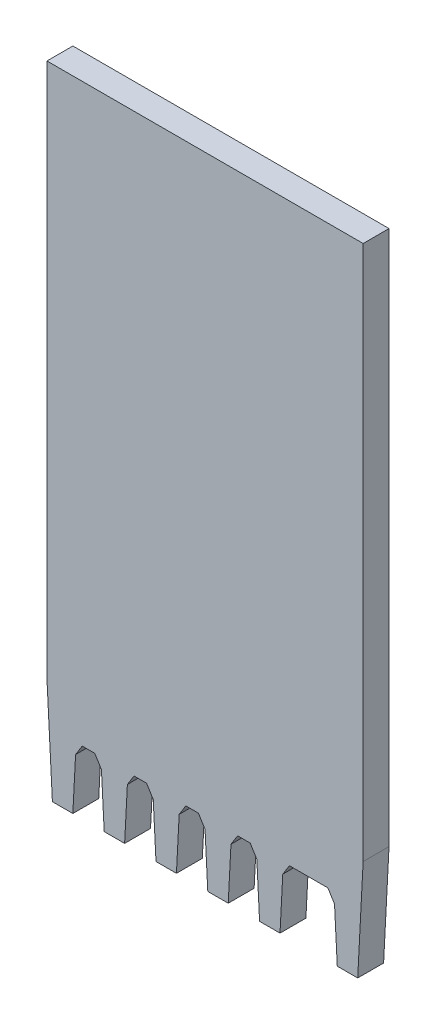
SolidWorks part; units mm, degrees
ref_plane "Front Plane" through (0, 0, 0) normal (0, 0, 1) x (1, 0, 0)
ref_plane "Top Plane" through (0, 0, 0) normal (0, 1, 0) x (1, 0, 0)
ref_plane "Right Plane" through (0, 0, 0) normal (1, 0, 0) x (0, 0, -1)
sketch "Sketch1" plane through (0, 0, 0) normal (0, 0, 1) x (1, 0, 0)
  line L0 (0, 0) -> (0, 37) construction
  line L1 (0, 37) -> (18.3124, 37) construction
  line L2 (18.3124, 37) -> (18.3124, 0) construction
  line L3 (18.3124, 0) -> (0, 0) construction
  line L4 (0, 3) -> (18.3124, 3) construction
  line L5 (0, 6) -> (18.3124, 6) construction
  line L6 (0.9062, 6) -> (0.9062, 0) construction
  line L7 (3.9062, 6) -> (3.9062, 0) construction
  line L8 (6.9062, 6) -> (6.9062, 0) construction
  line L9 (9.9062, 6) -> (9.9062, 0) construction
  line L10 (12.9062, 6) -> (12.9062, 0) construction
  line L11 (17.4062, 6) -> (17.4062, 0) construction
  line L12 (0.9062, 3) -> (3.9062, 3) construction
  line L13 (3.9062, 3) -> (6.9062, 3) construction
  line L14 (6.9062, 3) -> (9.9062, 3) construction
  line L15 (9.9062, 3) -> (12.9062, 3) construction
  line L16 (12.9062, 3) -> (17.4062, 3) construction
  line L17 (0.9062, 3) -> (0, 3) construction
  line L18 (17.4062, 3) -> (18.3124, 3) construction
  line L19 (2.4062, 3) -> (2.4062, 0) construction
  line L20 (5.4062, 3) -> (5.4062, 0) construction
  line L21 (8.4062, 3) -> (8.4062, 0) construction
  line L22 (11.4062, 3) -> (11.4062, 0) construction
  line L23 (15.1562, 3) -> (15.1562, 0) construction
  line L24 (14.4062, 3.75) -> (15.9062, 3.75) construction
  line L25 (0, 6) -> (0.3144, 0)
  line L26 (0.3144, 0) -> (1.4979, 0)
  line L27 (1.4979, 0) -> (1.6572, 3.0393)
  line L28 (3.1552, 3.0393) -> (3.3144, 0)
  line L29 (3.3144, 0) -> (4.4979, 0)
  line L30 (4.4979, 0) -> (4.6572, 3.0393)
  line L31 (6.1552, 3.0393) -> (6.3144, 0)
  line L32 (6.3144, 0) -> (7.4979, 0)
  line L33 (7.4979, 0) -> (7.6572, 3.0393)
  line L34 (9.1552, 3.0393) -> (9.3144, 0)
  line L35 (9.3144, 0) -> (10.4979, 0)
  line L36 (10.4979, 0) -> (10.6572, 3.0393)
  line L37 (12.1552, 3.0393) -> (12.3144, 0)
  line L38 (12.3144, 0) -> (13.4979, 0)
  line L39 (13.4979, 0) -> (13.6572, 3.0393)
  line L40 (16.6552, 3.0393) -> (16.8144, 0)
  line L41 (16.8144, 0) -> (17.9979, 0)
  line L42 (17.9979, 0) -> (18.3124, 6)
  line L44 (1.6572, 3.0393) -> (2.0426, 3.656)
  line L45 (0, 6) -> (0, 37)
  line L46 (0, 37) -> (18.3124, 37)
  line L47 (18.3124, 37) -> (18.3124, 6)
  line L48 (9.1562, 37) -> (9.1562, 6) construction
  line L49 (2.0426, 3.656) -> (2.7698, 3.656)
  line L50 (2.7698, 3.656) -> (3.1552, 3.0393)
  line L51 (4.6572, 3.0393) -> (5.0426, 3.656)
  line L52 (5.0426, 3.656) -> (5.7698, 3.656)
  line L53 (5.7698, 3.656) -> (6.1552, 3.0393)
  line L54 (7.6572, 3.0393) -> (8.0426, 3.656)
  line L55 (8.0426, 3.656) -> (8.7698, 3.656)
  line L56 (8.7698, 3.656) -> (9.1552, 3.0393)
  line L57 (10.6572, 3.0393) -> (11.0426, 3.656)
  line L58 (11.0426, 3.656) -> (11.7698, 3.656)
  line L59 (11.7698, 3.656) -> (12.1552, 3.0393)
  line L60 (13.6572, 3.0393) -> (14.0426, 3.656)
  line L61 (14.0426, 3.656) -> (16.2698, 3.656)
  line L62 (16.2698, 3.656) -> (16.6552, 3.0393)
  arc A0 (3.1552, 3.0393) -> (1.6572, 3.0393) centre (2.4062, 3) ccw construction
  arc A1 (6.1552, 3.0393) -> (4.6572, 3.0393) centre (5.4062, 3) ccw construction
  arc A2 (9.1552, 3.0393) -> (7.6572, 3.0393) centre (8.4062, 3) ccw construction
  arc A3 (12.1552, 3.0393) -> (10.6572, 3.0393) centre (11.4062, 3) ccw construction
  arc A4 (13.6572, 3.0393) -> (14.4062, 3.75) centre (14.4062, 3) cw construction
  arc A5 (16.6552, 3.0393) -> (15.9062, 3.75) centre (15.9062, 3) ccw construction
  dimension "D7" = 0.75
  dimension "D1" = 3
  dimension "D2" = 6
  dimension "D3" = 31
  dimension "D4" = 3
  dimension "D6" = 4.5
  dimension "D8" = 3
  dimension "D9" = 18.3124
  dimension "D10" = 37
extrude "Boss-Extrude1" add sketch "Sketch1" along normal blind 1.5
sketch "Sketch3" plane through (0, 0, 0) normal (0, 0, 1) x (1, 0, 0)
  line L0 (-0.4005, 6) -> (18.7129, 6)
  line L1 (18.7129, 3) -> (-0.4005, 3) construction
  line L2 (-0.4005, 0) -> (18.7129, 0) construction
  line L3 (-0.4005, -0.5) -> (18.7129, -0.5) construction
  line L4 (18.7129, -0.5) -> (18.7129, 6) construction
  line L5 (-0.4005, 6) -> (-0.4005, -0.5) construction
  line L6 (18.3124, 0) -> (0, 0) construction
  line L7 (0, 3) -> (18.3124, 3) construction
  line L8 (0, 6) -> (18.3124, 6) construction
  line L9 (0.3407, -0.5) -> (0, 6) construction
  line L10 (18.3124, 6) -> (17.9717, -0.5) construction
  line L11 (17.9979, 0) -> (18.3124, 6) construction
  line L12 (0, 6) -> (0.3144, 0) construction
  line L13 (5.4062, 6) -> (5.4062, -0.5) construction
  line L14 (3.9062, 6) -> (3.9062, -0.5) construction
  line L15 (5.4062, 3) -> (5.4062, 0) construction
  line L16 (3.1572, 3) -> (3.3407, -0.5) construction
  line L17 (2.7567, 3) -> (2.9401, -0.5)
  line L18 (3.1552, 3.0393) -> (3.3144, 0) construction
  line L19 (2.9401, -0.5) -> (4.8723, -0.5)
  line L20 (4.8723, -0.5) -> (5.0557, 3)
  line L21 (2.8484, 1.25) -> (3.2478, 1.2709) construction
  line L22 (5.9401, -0.5) -> (5.7567, 3)
  line L26 (7.8723, -0.5) -> (5.9401, -0.5)
  line L27 (8.0557, 3) -> (7.8723, -0.5)
  line L30 (2.4062, -0.5) -> (2.4062, 6) construction
  line L31 (2.4062, 3) -> (2.4062, 0) construction
  line L32 (8.4062, 6) -> (8.4062, -0.5) construction
  line L34 (11.4062, -0.5) -> (11.4062, 6) construction
  line L35 (15.1562, -0.5) -> (15.1562, 6) construction
  line L36 (8.4062, 3) -> (8.4062, 0) construction
  line L37 (11.4062, 3) -> (11.4062, 0) construction
  line L38 (15.1562, 3) -> (15.1562, 0) construction
  line L39 (10.8723, -0.5) -> (11.0557, 3)
  line L40 (8.9401, -0.5) -> (10.8723, -0.5)
  line L41 (8.7567, 3) -> (8.9401, -0.5)
  line L42 (11.9401, -0.5) -> (11.7567, 3)
  line L43 (13.8723, -0.5) -> (11.9401, -0.5)
  line L44 (14.0557, 3) -> (13.8723, -0.5)
  line L45 (16.4401, -0.5) -> (18.3723, -0.5)
  line L46 (16.2567, 3) -> (16.4401, -0.5)
  line L47 (18.3723, -0.5) -> (18.7129, 6)
  line L48 (1.8723, -0.5) -> (-0.0599, -0.5)
  line L49 (2.0557, 3) -> (1.8723, -0.5)
  line L50 (-0.0599, -0.5) -> (-0.4005, 6)
  line L51 (16.2567, 3) -> (14.0557, 3)
  line L52 (11.7567, 3) -> (11.0557, 3)
  line L53 (8.7567, 3) -> (8.0557, 3)
  line L54 (5.7567, 3) -> (5.0557, 3)
  line L55 (2.7567, 3) -> (2.0557, 3)
  dimension "D1" = 0.5
  dimension "D2" = 0.4
ref_plane "Plane1" through (3.9062, 0, 0) normal (1, 0, 0) x (0, 0, -1)
sketch "Sketch4" plane through (3.9062, 0, 0) normal (1, 0, 0) x (0, 0, -1)
  line L0 (0, 6) -> (0, -0.5) construction
  line L1 (0.6, 6) -> (-2.1, 6) construction
  line L2 (0.6, 6) -> (0.6, -0.5) construction
  line L3 (0.6, -0.5) -> (-2.1, -0.5) construction
  line L4 (-2.1, 6) -> (-2.1, -0.5) construction
  line L5 (-0.75, -0.5) -> (-0.75, 6) construction
  line L6 (-1.5, 6) -> (-1.5, -0.5) construction
  line L7 (0.6, 2.4005) -> (-2.1, 2.4005) construction
  line L8 (0.3, 6) -> (0.3, -0.5) construction
  line L9 (0.6, 2.4005) -> (3.846, 6) construction
  line L10 (2.2302, 6) -> (0.6, 4.1923) construction
  line L11 (0.6, 4.1923) -> (1.7139, 3.1878) construction
  line L12 (1.7139, 3.1878) -> (4.25, 6)
  line L13 (4.25, 6) -> (0.6, 6) construction
  line L14 (0.3, 1) -> (-1.8, 1) construction
  line L15 (-2.1, 0) -> (0.6, 0) construction
  line L16 (1.7139, 3.1878) -> (1.4912, 3.3887)
  line L17 (1.4912, 3.3887) -> (0.6, 2.4005)
  line L18 (-3.2139, 3.1878) -> (-5.75, 6)
  line L19 (-3.2139, 3.1878) -> (-2.9912, 3.3887)
  line L20 (-2.9912, 3.3887) -> (-2.1, 2.4005)
  line L21 (-2.1, 6) -> (-5.75, 6) construction
  line L22 (0.6, 3.0724) -> (3.2401, 6) construction
  arc A0 (0.4965, 2.2224) -> (0.6, -0.5) centre (4.2, 1) ccw
  arc A1 (0.6, 2.4005) -> (0.4965, 2.2224) centre (0.9713, 2.0656) ccw
  arc A2 (-2.1, 2.4005) -> (-1.9965, 2.2224) centre (-2.4713, 2.0656) cw
  arc A3 (-1.9965, 2.2224) -> (-2.1, -0.5) centre (-5.7, 1) cw
  dimension "D6" = 0.5
  dimension "D1" = 0.6
  dimension "D2" = 0.3
  dimension "D3" = 1.5
  dimension "D4" = 1
  dimension "D5" = 0.3
  dimension "D7" = 10
sketch "Sketch5" plane through (0, 0, 0) normal (1, 0, 0) x (0, 0, -1)
  line L0 (2.2302, 6) -> (0.6, 4.1923) construction
  line L1 (0.6, 4.1923) -> (1.7139, 3.1878) construction
  line L2 (1.7139, 3.1878) -> (4.25, 6) construction
  line L3 (2.2302, 6) -> (0.6, 4.1923) construction
  line L4 (0.6, 4.1923) -> (1.7139, 3.1878) construction
  line L5 (1.7139, 3.1878) -> (4.25, 6) construction
ref_plane "Plane2" through (0, 2.6105, -2.3541) normal (0, 0.7426, -0.6697) x (1, 0, 0)
sketch "Sketch6" plane through (0, 2.6105, -2.3541) normal (0, 0.7426, -0.6697) x (1, 0, 0)
  line L1 (3.9062, -2.362) -> (3.9062, -0.862) construction
  line L2 (3.9062, -2.362) -> (3.9062, -5.0612) construction
  line L3 (4.6562, -5.0612) -> (3.1562, -5.0612)
  line L4 (4.6562, -1.612) -> (3.1562, -1.612) construction
  line L5 (3.1562, -1.612) -> (3.1562, -5.0612)
  line L6 (4.6562, -1.612) -> (4.6562, -5.0612)
  line L10 (2.4062, -5.0612) -> (15.1562, -5.0612) construction
  line L11 (15.1562, -5.0612) -> (15.1562, -0.862) construction
  line L12 (15.1562, -0.862) -> (2.4062, -0.862) construction
  line L13 (2.4062, -0.862) -> (2.4062, -5.0612) construction
  line L14 (15.1562, 0.3349) -> (15.1562, -4.0182) construction
  line L15 (2.4062, 0.3349) -> (2.4062, -4.0182) construction
  line L16 (11.4062, -5.0612) -> (11.4062, -0.862) construction
  line L17 (8.4062, -5.0612) -> (8.4062, -0.862) construction
  line L18 (5.4062, -5.0612) -> (5.4062, -0.862) construction
  line L19 (5.4062, -4.0182) -> (5.4062, 0.3349) construction
  line L20 (8.4062, -4.0182) -> (8.4062, 0.3349) construction
  line L21 (11.4062, 0.3349) -> (11.4062, -4.0182) construction
  line L22 (0.1562, -1.612) -> (0.1562, -5.0612)
  line L23 (0.1562, -5.0612) -> (1.6562, -5.0612)
  line L24 (1.6562, -1.612) -> (1.6562, -5.0612)
  line L25 (7.6562, -1.612) -> (7.6562, -5.0612)
  line L26 (6.1562, -5.0612) -> (7.6562, -5.0612)
  line L27 (6.1562, -1.612) -> (6.1562, -5.0612)
  line L28 (10.6562, -1.612) -> (10.6562, -5.0612)
  line L29 (10.6562, -5.0612) -> (9.1562, -5.0612)
  line L30 (9.1562, -1.612) -> (9.1562, -5.0612)
  line L31 (13.6562, -1.612) -> (13.6562, -5.0612)
  line L32 (12.1562, -5.0612) -> (13.6562, -5.0612)
  line L33 (12.1562, -1.612) -> (12.1562, -5.0612)
  line L34 (18.1562, -1.612) -> (18.1562, -5.0612)
  line L35 (18.1562, -5.0612) -> (16.6562, -5.0612)
  line L36 (16.6562, -1.612) -> (16.6562, -5.0612)
  circle A0 centre (3.9062, -1.612) radius 0.75 construction
  arc A1 (4.6562, -1.612) -> (3.1562, -1.612) centre (3.9062, -1.612) ccw
  arc A2 (0.1562, -1.612) -> (1.6562, -1.612) centre (0.9062, -1.612) cw
  arc A3 (6.1562, -1.612) -> (7.6562, -1.612) centre (6.9062, -1.612) cw
  arc A4 (10.6562, -1.612) -> (9.1562, -1.612) centre (9.9062, -1.612) ccw
  arc A5 (12.1562, -1.612) -> (13.6562, -1.612) centre (12.9062, -1.612) cw
  arc A6 (18.1562, -1.612) -> (16.6562, -1.612) centre (17.4062, -1.612) ccw
ref_plane "Plane3" through (0, 1.6223, -1.463) normal (0, 0.7426, -0.6697) x (1, 0, 0)
sketch "Sketch7" plane through (0, 1.6223, -1.463) normal (0, 0.7426, -0.6697) x (1, 0, 0)
  line L0 (3.1562, -1.612) -> (3.1562, -5.0612) construction
  line L1 (4.6562, -5.0612) -> (3.1562, -5.0612) construction
  line L2 (4.6562, -1.612) -> (4.6562, -5.0612) construction
  line L3 (3.1562, -1.612) -> (3.1562, -5.0612) construction
  line L4 (4.6562, -5.0612) -> (3.1562, -5.0612) construction
  line L5 (4.6562, -1.612) -> (4.6562, -5.0612) construction
  line L6 (3.9062, -0.862) -> (3.9062, -5.0612) construction
  line L7 (4.6562, -1.612) -> (3.1562, -1.612) construction
  line L8 (4.6562, -2.362) -> (3.1562, -2.362) construction
  line L9 (3.4562, -1.612) -> (3.4562, -2.362)
  line L10 (3.4562, -2.362) -> (4.3562, -2.362)
  line L11 (4.3562, -2.362) -> (4.3562, -1.612)
  line L12 (2.4062, -0.862) -> (2.4062, -5.0612) construction
  line L13 (2.4062, -5.0612) -> (15.1562, -5.0612) construction
  line L14 (15.1562, -0.862) -> (2.4062, -0.862) construction
  line L15 (5.4062, -5.0612) -> (5.4062, -0.862) construction
  line L16 (8.4062, -5.0612) -> (8.4062, -0.862) construction
  line L17 (11.4062, -5.0612) -> (11.4062, -0.862) construction
  line L18 (15.1562, -5.0612) -> (15.1562, -0.862) construction
  line L19 (2.4062, -0.862) -> (2.4062, -5.0612) construction
  line L20 (2.4062, -5.0612) -> (15.1562, -5.0612) construction
  line L21 (15.1562, -0.862) -> (2.4062, -0.862) construction
  line L22 (5.4062, -5.0612) -> (5.4062, -0.862) construction
  line L23 (8.4062, -5.0612) -> (8.4062, -0.862) construction
  line L24 (11.4062, -5.0612) -> (11.4062, -0.862) construction
  line L25 (15.1562, -5.0612) -> (15.1562, -0.862) construction
  line L26 (0.4562, -2.362) -> (0.4562, -1.612)
  line L27 (1.3562, -2.362) -> (0.4562, -2.362)
  line L28 (1.3562, -1.612) -> (1.3562, -2.362)
  line L29 (7.3562, -2.362) -> (6.4562, -2.362)
  line L30 (7.3562, -1.612) -> (7.3562, -2.362)
  line L31 (6.4562, -2.362) -> (6.4562, -1.612)
  line L32 (9.4562, -1.612) -> (9.4562, -2.362)
  line L33 (10.3562, -2.362) -> (10.3562, -1.612)
  line L34 (9.4562, -2.362) -> (10.3562, -2.362)
  line L35 (13.3562, -1.612) -> (13.3562, -2.362)
  line L36 (12.4562, -2.362) -> (12.4562, -1.612)
  line L37 (13.3562, -2.362) -> (12.4562, -2.362)
  line L38 (16.9562, -1.612) -> (16.9562, -2.362)
  line L39 (17.8562, -2.362) -> (17.8562, -1.612)
  line L40 (16.9562, -2.362) -> (17.8562, -2.362)
  arc A0 (4.6562, -1.612) -> (3.1562, -1.612) centre (3.9062, -1.612) ccw construction
  arc A1 (4.6562, -1.612) -> (3.1562, -1.612) centre (3.9062, -1.612) ccw construction
  circle A2 centre (3.9062, -1.612) radius 0.45 construction
  arc A3 (4.3562, -1.612) -> (3.4562, -1.612) centre (3.9062, -1.612) ccw
  arc A4 (0.4562, -1.612) -> (1.3562, -1.612) centre (0.9062, -1.612) cw
  arc A5 (6.4562, -1.612) -> (7.3562, -1.612) centre (6.9062, -1.612) cw
  arc A6 (10.3562, -1.612) -> (9.4562, -1.612) centre (9.9062, -1.612) ccw
  arc A7 (12.4562, -1.612) -> (13.3562, -1.612) centre (12.9062, -1.612) cw
  arc A8 (17.8562, -1.612) -> (16.9562, -1.612) centre (17.4062, -1.612) ccw
ref_plane "bisect" through (0, 0, 0.75) normal (0, 0, 1) x (1, 0, 0)
ref_plane "insert_surface" through (0, 6, 0) normal (0, 1, 0) x (1, 0, 0)
sketch "Sketch8" plane through (0, 6, 0) normal (0, 1, 0) x (1, 0, 0)
  line L0 (18.7129, -0.75) -> (-0.4005, -0.75) construction
  line L1 (-0.4005, 0.6) -> (18.7129, 0.6)
  line L2 (-0.4005, 0.6) -> (-0.4005, -2.1)
  line L3 (-0.4005, -2.1) -> (18.7129, -2.1)
  line L4 (18.7129, 0.6) -> (18.7129, -2.1)
  line L5 (9.1562, 0.6) -> (9.1562, -2.1) construction
  line L6 (0, 0) -> (18.3124, 0) construction
  line L7 (0, 0) -> (0, -1.5) construction
  line L8 (0, -1.5) -> (18.3124, -1.5) construction
  line L9 (18.3124, 0) -> (18.3124, -1.5) construction
  line L10 (18.7129, 0.3) -> (-0.4005, 0.3) construction
  line L11 (18.7129, -1.8) -> (-0.4005, -1.8) construction
sketch "Sketch9" plane through (0, 0, 0) normal (0, 0, 1) x (1, 0, 0)
  line L0 (18.3723, -0.5) -> (18.7129, 6) construction
  line L1 (-0.4005, 6) -> (18.7129, 6) construction
  line L2 (-0.0599, -0.5) -> (-0.4005, 6) construction
  line L3 (1.8723, -0.5) -> (-0.0599, -0.5) construction
  line L4 (2.0557, 3) -> (1.8723, -0.5) construction
  line L5 (2.7567, 3) -> (2.0557, 3) construction
  line L6 (2.7567, 3) -> (2.9401, -0.5) construction
  line L7 (2.9401, -0.5) -> (4.8723, -0.5) construction
  line L8 (4.8723, -0.5) -> (5.0557, 3) construction
  line L9 (5.7567, 3) -> (5.0557, 3) construction
  line L10 (5.9401, -0.5) -> (5.7567, 3) construction
  line L11 (7.8723, -0.5) -> (5.9401, -0.5) construction
  line L12 (8.0557, 3) -> (7.8723, -0.5) construction
  line L13 (8.7567, 3) -> (8.0557, 3) construction
  line L14 (8.7567, 3) -> (8.9401, -0.5) construction
  line L15 (8.9401, -0.5) -> (10.8723, -0.5) construction
  line L16 (10.8723, -0.5) -> (11.0557, 3) construction
  line L17 (11.7567, 3) -> (11.0557, 3) construction
  line L18 (11.9401, -0.5) -> (11.7567, 3) construction
  line L19 (13.8723, -0.5) -> (11.9401, -0.5) construction
  line L20 (14.0557, 3) -> (13.8723, -0.5) construction
  line L21 (16.2567, 3) -> (14.0557, 3) construction
  line L22 (16.2567, 3) -> (16.4401, -0.5) construction
  line L23 (16.4401, -0.5) -> (18.3723, -0.5) construction
  line L24 (18.3723, -0.5) -> (18.7129, 6)
  line L25 (-0.4005, 6) -> (18.7129, 6) construction
  line L26 (-0.0599, -0.5) -> (-0.4005, 6)
  line L27 (1.8723, -0.5) -> (-0.0599, -0.5)
  line L28 (2.0557, 3) -> (1.8723, -0.5)
  line L29 (2.7567, 3) -> (2.0557, 3) construction
  line L30 (2.7567, 3) -> (2.9401, -0.5)
  line L31 (2.9401, -0.5) -> (4.8723, -0.5)
  line L32 (4.8723, -0.5) -> (5.0557, 3)
  line L33 (5.7567, 3) -> (5.0557, 3) construction
  line L34 (5.9401, -0.5) -> (5.7567, 3)
  line L35 (7.8723, -0.5) -> (5.9401, -0.5)
  line L36 (8.0557, 3) -> (7.8723, -0.5)
  line L37 (8.7567, 3) -> (8.0557, 3) construction
  line L38 (8.7567, 3) -> (8.9401, -0.5)
  line L39 (8.9401, -0.5) -> (10.8723, -0.5)
  line L40 (10.8723, -0.5) -> (11.0557, 3)
  line L41 (11.7567, 3) -> (11.0557, 3) construction
  line L42 (11.9401, -0.5) -> (11.7567, 3)
  line L43 (13.8723, -0.5) -> (11.9401, -0.5)
  line L44 (14.0557, 3) -> (13.8723, -0.5)
  line L45 (16.2567, 3) -> (14.0557, 3) construction
  line L46 (16.2567, 3) -> (16.4401, -0.5)
  line L47 (16.4401, -0.5) -> (18.3723, -0.5)
  line L48 (16.2567, 3) -> (16.2567, 6)
  line L49 (14.0557, 3) -> (14.0557, 6)
  line L50 (11.7567, 3) -> (11.7567, 6)
  line L51 (18.7129, 6) -> (-0.4005, 6) construction
  line L52 (11.0557, 3) -> (11.0557, 6)
  line L53 (-0.4005, 6) -> (18.7129, 6) construction
  line L54 (8.7567, 3) -> (8.7567, 6)
  line L55 (8.0557, 3) -> (8.0557, 6)
  line L58 (5.7567, 3) -> (5.7567, 6)
  line L60 (5.0557, 3) -> (5.0557, 6)
  line L62 (15.1562, -0.5) -> (15.1562, 6) construction
  line L63 (15.1562, -0.5) -> (15.1562, 6) construction
  line L64 (2.7567, 3) -> (2.7567, 6)
  line L65 (2.0557, 3) -> (2.0557, 6)
  line L67 (18.7129, 6) -> (16.2567, 6)
  line L68 (14.0557, 6) -> (11.7567, 6)
  line L69 (11.0557, 6) -> (8.7567, 6)
  line L70 (8.0557, 6) -> (5.7567, 6)
  line L71 (5.0557, 6) -> (2.7567, 6)
  line L72 (2.0557, 6) -> (-0.4005, 6)
sketch "Sketch10" plane through (0, 6, 0) normal (0, 1, 0) x (1, 0, 0)
  line L0 (9.1562, -5.75) -> (9.1562, -0.75) construction
  line L1 (-0.8438, 4.25) -> (19.1562, 4.25)
  line L2 (-0.8438, 4.25) -> (-0.8438, -5.75)
  line L3 (-0.8438, -5.75) -> (19.1562, -5.75)
  line L4 (19.1562, 4.25) -> (19.1562, -5.75)
  line L5 (9.1562, -0.75) -> (9.1562, 4.25) construction
  line L6 (9.1562, -0.75) -> (19.1562, -0.75) construction
  line L7 (9.1562, -0.75) -> (-0.8438, -0.75) construction
  line L8 (-10.5124, -0.75) -> (10.5124, -0.75) construction
  dimension "D1" = 10
  dimension "D2" = 20
ref_plane "right_center" through (9.1562, 0, 0) normal (1, 0, 0) x (0, 0, -1)
